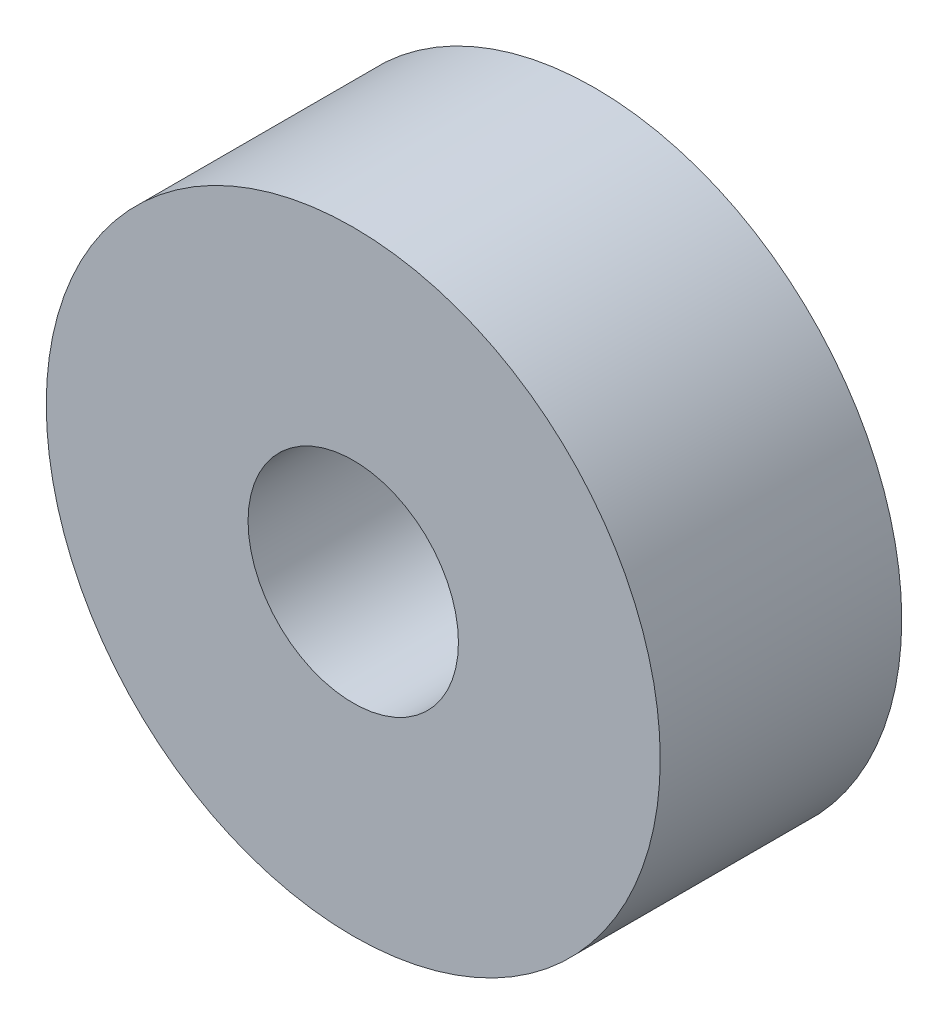
SolidWorks part; units mm, degrees
material "6061-T6 (SS)"
ref_plane "Front Plane" through (0, 0, 0) normal (0, 0, 1) x (1, 0, 0)
ref_plane "Top Plane" through (0, 0, 0) normal (0, 1, 0) x (1, 0, 0)
ref_plane "Right Plane" through (0, 0, 0) normal (1, 0, 0) x (0, 0, -1)
sketch "Sketch1" plane through (0, 0, 0) normal (1, 0, 0) x (0, 0, -1)
  line L0 (21.7309, 0) -> (-28.9169, 0) construction
  line L1 (-3.7465, 9.525) -> (-3.7465, 3.2639)
  line L2 (-3.7465, 9.525) -> (3.7465, 9.525)
  line L3 (-3.7465, 3.2639) -> (3.7465, 3.2639)
  line L4 (3.7465, 9.525) -> (3.7465, 3.2639)
  point P3 (0, 3.2639)
  dimension "D1" = 19.05
  dimension "D2" = 6.5278
  dimension "D3" = 7.493
revolve "Revolve1" add sketch "Sketch1" angle 360 about L0
